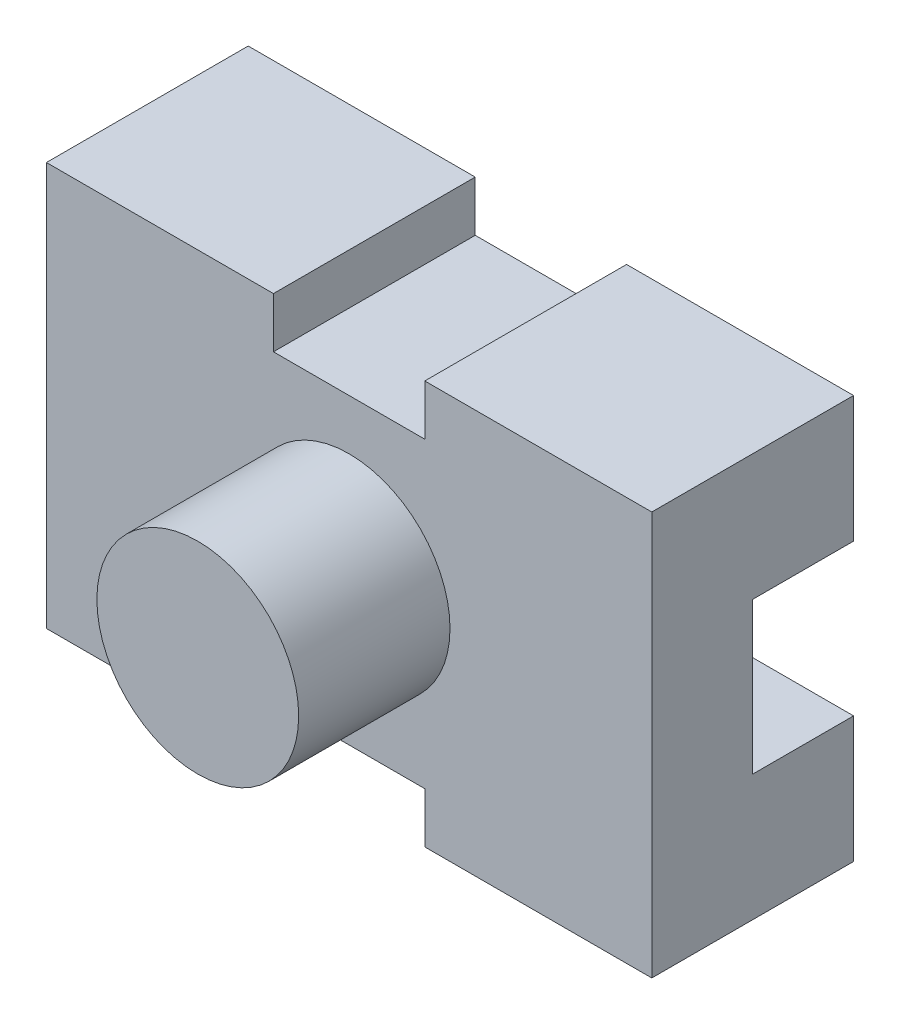
SolidWorks part; units mm, degrees
material "Сталь"
ref_plane "Спереди" through (0, 0, 0) normal (0, 0, 1) x (1, 0, 0)
ref_plane "Сверху" through (0, 0, 0) normal (0, 1, 0) x (1, 0, 0)
ref_plane "Справа" through (0, 0, 0) normal (1, 0, 0) x (0, 0, -1)
sketch "Эскиз1" plane through (0, 0, 0) normal (0, 0, 1) x (1, 0, 0)
  line L1 (-30, -20) -> (30, -20)
  line L2 (-30, -20) -> (-30, 20)
  line L3 (-30, 20) -> (30, 20)
  line L4 (30, -20) -> (30, 20)
  line L5 (-30, -20) -> (30, 20) construction
  line L6 (-30, 20) -> (30, -20) construction
  point P0 (0, 0)
  dimension "D1" = 40
  dimension "D2" = 60
extrude "Бобышка-Вытянуть1" add sketch "Эскиз1" along normal blind 20
sketch "Эскиз2" plane through (0, 0, 20) normal (0, 0, 1) x (1, 0, 0)
  circle A0 centre (0, 0) radius 10
  dimension "D1" = 20
extrude "Бобышка-Вытянуть2" add sketch "Эскиз2" along normal blind 15
sketch "Эскиз3" plane through (0, 0, 20) normal (0, 0, 1) x (1, 0, 0)
  line L0 (0, 20) -> (0, -20) construction
  line L1 (30, 20) -> (-30, 20) construction
  line L2 (-30, -20) -> (30, -20) construction
  line L4 (-7.5, -15) -> (7.5, -15)
  line L5 (-7.5, -15) -> (-7.5, -20)
  line L6 (-7.5, -20) -> (7.5, -20)
  line L7 (7.5, -15) -> (7.5, -20)
  line L8 (-7.5, -15) -> (7.5, -20) construction
  line L9 (-7.5, -20) -> (7.5, -15) construction
  point P6 (0, -17.5)
  dimension "D1" = 15
  dimension "D2" = 5
extrude "Вырез-Вытянуть1" cut sketch "Эскиз3" against normal through all
mirror "Зеркальное отражение1" about plane through (0, 0, 0) normal (0, 1, 0) of "Вырез-Вытянуть1"
sketch "Эскиз4" plane through (-30, 0, 0) normal (-1, 0, 0) x (0, 0, 1)
  line L0 (0, 0) -> (20, 0) construction
  line L1 (0, 20) -> (0, -20) construction
  line L2 (20, 20) -> (20, -20) construction
  line L4 (10, -7.5) -> (0, -7.5)
  line L5 (10, -7.5) -> (10, 7.5)
  line L6 (10, 7.5) -> (0, 7.5)
  line L7 (0, -7.5) -> (0, 7.5)
  line L8 (10, -7.5) -> (0, 7.5) construction
  line L9 (10, 7.5) -> (0, -7.5) construction
  point P6 (5, 0)
  dimension "D1" = 15
  dimension "D2" = 10
extrude "Вырез-Вытянуть2" cut sketch "Эскиз4" against normal through all
